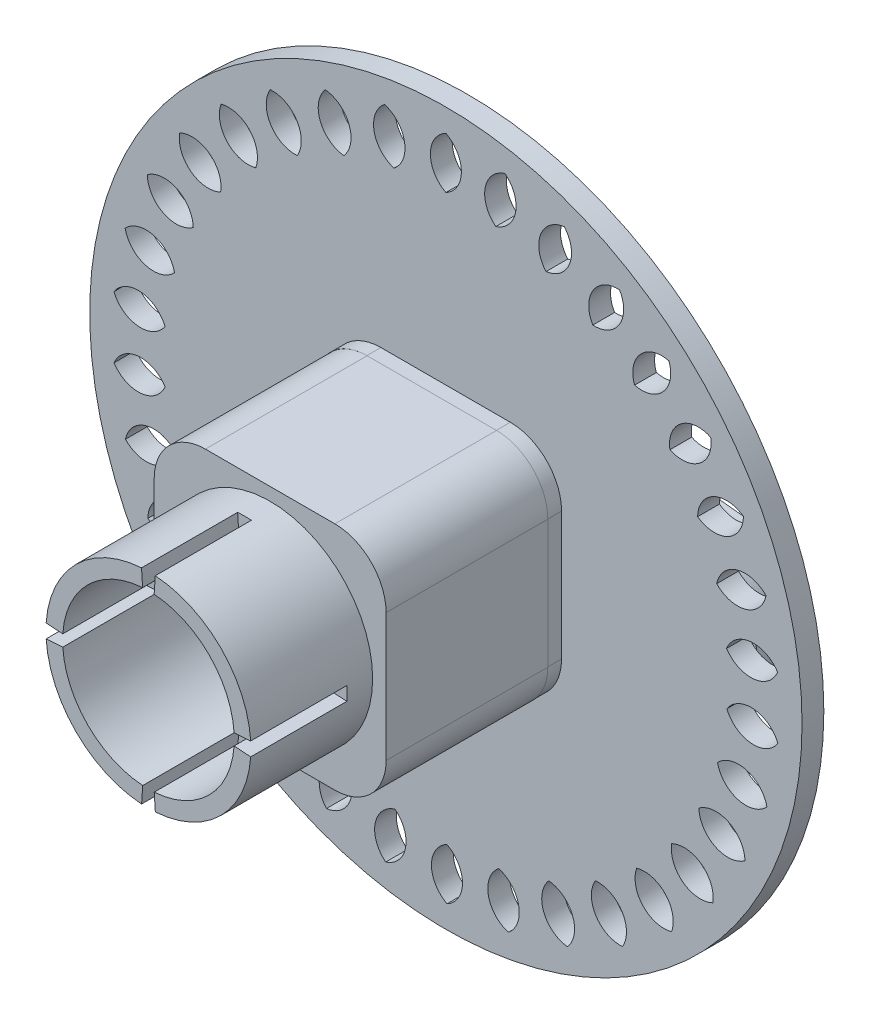
SolidWorks part; units mm, degrees
ref_plane "Front Plane" through (0, 0, 0) normal (0, 0, 1) x (1, 0, 0)
ref_plane "Top Plane" through (0, 0, 0) normal (0, 1, 0) x (1, 0, 0)
ref_plane "Right Plane" through (0, 0, 0) normal (1, 0, 0) x (0, 0, -1)
sketch "Sketch1" plane through (0, 0, 0) normal (0, 0, 1) x (1, 0, 0)
  line L12 (-5.05, 9.0001) -> (5.05, 9.0001)
  line L13 (-9.05, 5.0001) -> (-9.05, -5.0001)
  line L14 (-5.05, -9.0001) -> (5.05, -9.0001)
  line L15 (9.05, 5.0001) -> (9.05, -5.0001)
  line L16 (-9.05, 9.0001) -> (9.05, -9.0001) construction
  line L17 (-9.05, -9.0001) -> (9.05, 9.0001) construction
  arc A4 (-9.05, -5.0001) -> (-5.05, -9.0001) centre (-5.05, -5.0001) ccw
  arc A5 (5.05, -9.0001) -> (9.05, -5.0001) centre (5.05, -5.0001) ccw
  arc A6 (5.05, 9.0001) -> (9.05, 5.0001) centre (5.05, 5.0001) cw
  arc A7 (-5.05, 9.0001) -> (-9.05, 5.0001) centre (-5.05, 5.0001) ccw
  point P0 (0, 0)
  dimension "D2" = 4
  dimension "D1" = 9.05
extrude "Boss-Extrude1" add sketch "Sketch1" along normal blind 2
sketch "Sketch2" plane through (0, 0, 0) normal (0, 0, 1) x (1, 0, 0)
  line L0 (-5.05, 9.0001) -> (5.05, 9.0001)
  line L1 (-9.05, 5.0001) -> (-9.05, -5.0001)
  line L2 (-5.05, -9.0001) -> (5.05, -9.0001)
  line L3 (9.05, 5.0001) -> (9.05, -5.0001)
  line L4 (-9.05, 9.0001) -> (9.05, -9.0001) construction
  line L5 (-9.05, -9.0001) -> (9.05, 9.0001) construction
  arc A0 (-9.05, -5.0001) -> (-5.05, -9.0001) centre (-5.05, -5.0001) ccw
  arc A1 (5.05, -9.0001) -> (9.05, -5.0001) centre (5.05, -5.0001) ccw
  arc A2 (5.05, 9.0001) -> (9.05, 5.0001) centre (5.05, 5.0001) cw
  arc A3 (-5.05, 9.0001) -> (-9.05, 5.0001) centre (-5.05, 5.0001) ccw
  point P0 (0, 0)
  dimension "D2" = 4
  dimension "D1" = 9.05
extrude "Boss-Extrude2" add sketch "Sketch2" along normal blind 11.02
sketch "Sketch3" plane through (0, 0, 11.02) normal (0, 0, 1) x (1, 0, 0)
  line L1 (-5.05, 9.0001) -> (5.05, 9.0001)
  line L2 (-9.05, 5.0001) -> (-9.05, -5.0001)
  line L3 (-5.05, -9.0001) -> (5.05, -9.0001)
  line L4 (9.05, 5.0001) -> (9.05, -5.0001)
  line L5 (-9.05, 9.0001) -> (9.05, -9.0001) construction
  line L6 (-9.05, -9.0001) -> (9.05, 9.0001) construction
  arc A0 (-9.05, -5.0001) -> (-5.05, -9.0001) centre (-5.05, -5.0001) ccw
  arc A1 (5.05, -9.0001) -> (9.05, -5.0001) centre (5.05, -5.0001) ccw
  arc A2 (5.05, 9.0001) -> (9.05, 5.0001) centre (5.05, 5.0001) cw
  arc A3 (-5.05, 9.0001) -> (-9.05, 5.0001) centre (-5.05, 5.0001) ccw
  point P0 (0, 0)
  dimension "D2" = 4
  dimension "D1" = 9.05
extrude "Boss-Extrude3" add sketch "Sketch3" along normal blind 1.6
sketch "Sketch4" plane through (0, 0, 12.62) normal (0, 0, 1) x (1, 0, 0)
  circle A1 centre (0, 0) radius 8
  dimension "D2" = 16
extrude "Boss-Extrude4" add sketch "Sketch4" along normal blind 9.5
sketch "Sketch5" plane through (0, 0, 12.62) normal (0, 0, 1) x (1, 0, 0)
  circle A0 centre (0, 0) radius 6.65
  dimension "D1" = 13.3
extrude "Cut-Extrude1" cut sketch "Sketch5" along normal blind 20
sketch "Sketch12" plane through (0, 0, 0) normal (0, 0, -1) x (-1, 0, 0)
  line L0 (-5.0274, 8.9973) -> (5.0726, 8.9973)
  line L1 (-9.0274, 4.9973) -> (-9.0274, -5.0029)
  line L2 (-5.0274, -9.0029) -> (5.0726, -9.0029)
  line L3 (9.0726, 4.9973) -> (9.0726, -5.0029)
  line L4 (-9.0274, 8.9973) -> (9.0726, -9.0029) construction
  line L5 (-9.0274, -9.0029) -> (9.0726, 8.9973) construction
  arc A0 (-9.0274, -5.0029) -> (-5.0274, -9.0029) centre (-5.0274, -5.0029) ccw
  arc A1 (5.0726, -9.0029) -> (9.0726, -5.0029) centre (5.0726, -5.0029) ccw
  arc A2 (5.0726, 8.9973) -> (9.0726, 4.9973) centre (5.0726, 4.9973) cw
  arc A3 (-5.0274, 8.9973) -> (-9.0274, 4.9973) centre (-5.0274, 4.9973) ccw
  point P0 (0.0226, -0.0028)
  dimension "D2" = 4
  dimension "D1" = 9.05
extrude "Boss-Extrude5" add sketch "Sketch12" along normal blind 1.095 contours L0 A2 L3 A1 L2 A0 L1 A3
sketch "Sketch13" plane through (0, 0, 0) normal (0, 0, 1) x (1, 0, 0)
  circle A0 centre (0, 0) radius 6.7
  dimension "D1" = 13.4
extrude "Cut-Extrude3" cut sketch "Sketch13" against normal mid plane 60
sketch "Sketch15" plane through (0, 0, 22.12) normal (0, 0, 1) x (1, 0, 0)
  line L1 (-0.5528, 8.1871) -> (-0.0028, 0.0033)
  line L3 (0.5472, 8.1871) -> (-0.0028, 0.0033)
  line L4 (-0.5528, 8.1871) -> (-0.626, 9.0001)
  line L5 (5.05, 9.0001) -> (-5.05, 9.0001) construction
  line L6 (-0.626, 9.0001) -> (0.6172, 9.0001)
  line L7 (0.6172, 9.0001) -> (0.5472, 8.1871)
  dimension "D3" = 0.0732
  dimension "D4" = 0.07
extrude "Cut-Extrude4" cut sketch "Sketch15" against normal blind 7.5 contours L1 L3 L7 L6 L4
pattern_circular "CirPattern2" count 4 over 360 about axis through (0, 0, 0) along (0, 0, 1) of "Cut-Extrude4"
sketch "Sketch16" plane through (0, 0, -1.095) normal (0, 0, -1) x (-1, 0, 0)
  line L4 (-5.0236, 8.9395) -> (5.0767, 8.9395)
  line L6 (-5.0234, -8.9918) -> (5.0766, -8.9918)
  line L12 (-9.0234, 9.0084) -> (9.0766, -8.9918) construction
  line L13 (-9.0234, -8.9918) -> (9.0766, 9.0084) construction
  line L14 (0.0266, 0.0083) -> (0.0266, 11.7541) construction
  line L19 (-9.0274, 4.8569) -> (-19.0274, 4.8569)
  line L20 (-9.0274, 4.9973) -> (-9.0274, -5.0029) construction
  line L27 (-19.0274, 4.8569) -> (-19.0274, -4.7841)
  line L28 (-19.0274, -4.7841) -> (-9.0274, -4.7841)
  line L29 (-9.0274, 4.8569) -> (-9.0236, 4.9395)
  line L30 (-9.0274, -4.7841) -> (-9.0234, -4.9857)
  line L34 (9.0726, 4.8569) -> (19.0726, 4.8569)
  line L35 (9.0726, 4.9973) -> (9.0726, -5.0029) construction
  line L36 (19.0726, 4.8569) -> (19.0726, -4.8255)
  line L37 (19.0726, -4.8255) -> (9.0726, -4.8255)
  line L38 (9.0726, -4.8255) -> (9.0766, -4.9857)
  line L39 (9.0726, 4.8569) -> (9.0767, 4.9395)
  arc A6 (-9.0234, -4.9857) -> (-5.0234, -8.9918) centre (-5.0234, -4.9918) ccw
  arc A7 (5.0766, -8.9918) -> (9.0766, -4.9857) centre (5.0766, -4.9918) ccw
  arc A8 (5.0767, 8.9395) -> (9.0767, 4.9395) centre (5.0767, 4.9395) cw
  arc A9 (-5.0236, 8.9395) -> (-9.0236, 4.9395) centre (-5.0236, 4.9395) ccw
  point P0 (0.0266, 0.0083)
  point P17 (0.0266, 0.0083)
  point P23 (-13.5773, 0)
  point P32 (13.4528, 0.0083)
  point P34 (13.4528, 0.0083)
  dimension "D2" = 4
  dimension "D3" = 10
  dimension "D1" = 10
extrude "Boss-Extrude6" add sketch "Sketch16" along normal blind 2.5 separate body
sketch "Sketch17" plane through (0, 0, -3.595) normal (0, 0, -1) x (-1, 0, 0)
  line L0 (0, 7) -> (-19, 5)
  line L1 (-19, -5) -> (0, -7)
  line L2 (0, -7) -> (19, -7)
  line L3 (0, 7) -> (19, 7)
  line L4 (0, 3.7) -> (-16, 2.2)
  line L5 (-16, -2.2) -> (0, -3.7)
  line L6 (0, -3.7) -> (16, -3.8)
  line L7 (0, 3.7) -> (16, 3.8)
  line L8 (19, 7) -> (16, 3.8)
  line L9 (16, -3.8) -> (19, -7)
  arc A1 (-19, 5) -> (-19, -5) centre (-15.9375, 0) ccw
  arc A4 (-16, 2.2) -> (-16, -2.2) centre (-15, 0) ccw
  dimension "D2" = 2.2
  dimension "D3" = 2
  dimension "D4" = 2
  dimension "D5" = 0
  dimension "D6" = 16
  dimension "D7" = 1.5
  dimension "D8" = 1.5
  dimension "D9" = 19
  dimension "D10" = 19
  dimension "D11" = 2.2
  dimension "D12" = 5
  dimension "D13" = 5
  dimension "16" = 16
  dimension "D14" = 19
  dimension "D15" = 16
  dimension "D16" = 16
  dimension "D17" = 19
  dimension "D18" = 0
  dimension "D19" = 0
  dimension "D20" = 0
  dimension "D21" = 0
  dimension "D22" = 0
  dimension "D23" = 0.1
  dimension "D24" = 0.1
extrude "Boss-Extrude7" add sketch "Sketch17" along normal blind 4
sketch "Sketch18" plane through (0, 0, -1.095) normal (0, 0, 1) x (1, 0, 0)
  circle A0 centre (0, 0) radius 27.7985
extrude "Boss-Extrude8" add sketch "Sketch18" against normal blind 1.7
sketch "Sketch19" plane through (0, 0, -1.095) normal (0, 0, 1) x (1, 0, 0)
  line L0 (0, 0) -> (0, 31.7696) construction
  arc A1 (0, 26.0168) -> (0, 22.0102) centre (-1.053, 24.0135) cw
  arc A2 (0, 26.0168) -> (0, 22.0102) centre (1.053, 24.0135) ccw
extrude "Cut-Extrude5" cut sketch "Sketch19" against normal blind 2.5
pattern_circular "CirPattern3" count 34 every 10.6 about axis through (0, 0, 0) along (0, 0, 1) of "Cut-Extrude5"
sketch "Sketch20" plane through (0, 0, -3.595) normal (0, 0, -1) x (-1, 0, 0)
  circle A0 centre (0, 0) radius 3.5494
extrude "Cut-Extrude6" cut sketch "Sketch20" against normal blind 3
